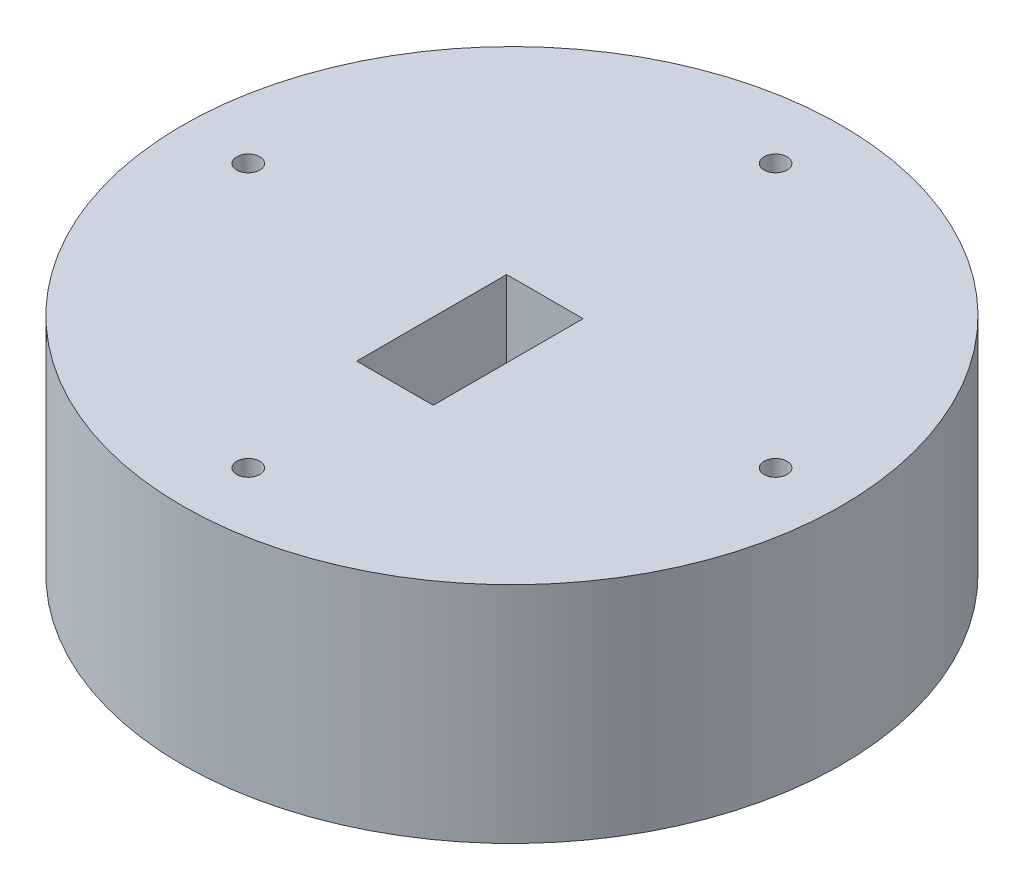
SolidWorks part; units mm, degrees
material "6061 Alloy"
ref_plane "Front Plane" through (0, 0, 0) normal (0, 0, 1) x (1, 0, 0)
ref_plane "Top Plane" through (0, 0, 0) normal (0, 1, 0) x (1, 0, 0)
ref_plane "Right Plane" through (0, 0, 0) normal (1, 0, 0) x (0, 0, -1)
sketch "Sketch1" plane through (0, 0, 0) normal (0, 1, 0) x (1, 0, 0)
  circle A0 centre (0, 0) radius 50
  dimension "D1" = 100
extrude "Boss-Extrude1" add sketch "Sketch1" along normal blind 30
sketch "Sketch2" plane through (0, 30, 0) normal (0, 1, 0) x (1, 0, 0)
  circle A0 centre (0, 0) radius 50
  dimension "D1" = 100
extrude "Boss-Extrude2" add sketch "Sketch2" along normal blind 4
sketch "Sketch3" plane through (0, 34, 0) normal (0, 1, 0) x (1, 0, 0)
  line L1 (-5.8, 5) -> (5.8, 5)
  line L2 (-5.8, 5) -> (-5.8, -17.75)
  line L3 (-5.8, -17.75) -> (5.8, -17.75)
  line L4 (5.8, 5) -> (5.8, -17.75)
  line L5 (-5.8, 5) -> (5.8, -17.75) construction
  line L6 (-5.8, -17.75) -> (5.8, 5) construction
  point P0 (0, -6.375)
  point P8 (0, -17.75)
  dimension "D1" = 6.375
  dimension "D2" = 11.6
  dimension "D3" = 22.75
extrude "Cut-Extrude1" cut sketch "Sketch3" against normal blind 14
sketch "Sketch5" plane through (0, 34, 0) normal (0, 1, 0) x (1, 0, 0)
  circle A0 centre (0, 0) radius 40 construction
  circle A1 centre (0, 40) radius 1.75
  circle A2 centre (40, 0) radius 1.75
  circle A3 centre (0, -40) radius 1.75
  circle A4 centre (-40, 0) radius 1.75
  point P14 (0, 0)
  dimension "D1" = 80
  dimension "D2" = 3.5
  dimension "D3" = 4
extrude "Cut-Extrude3" cut sketch "Sketch5" against normal through all
